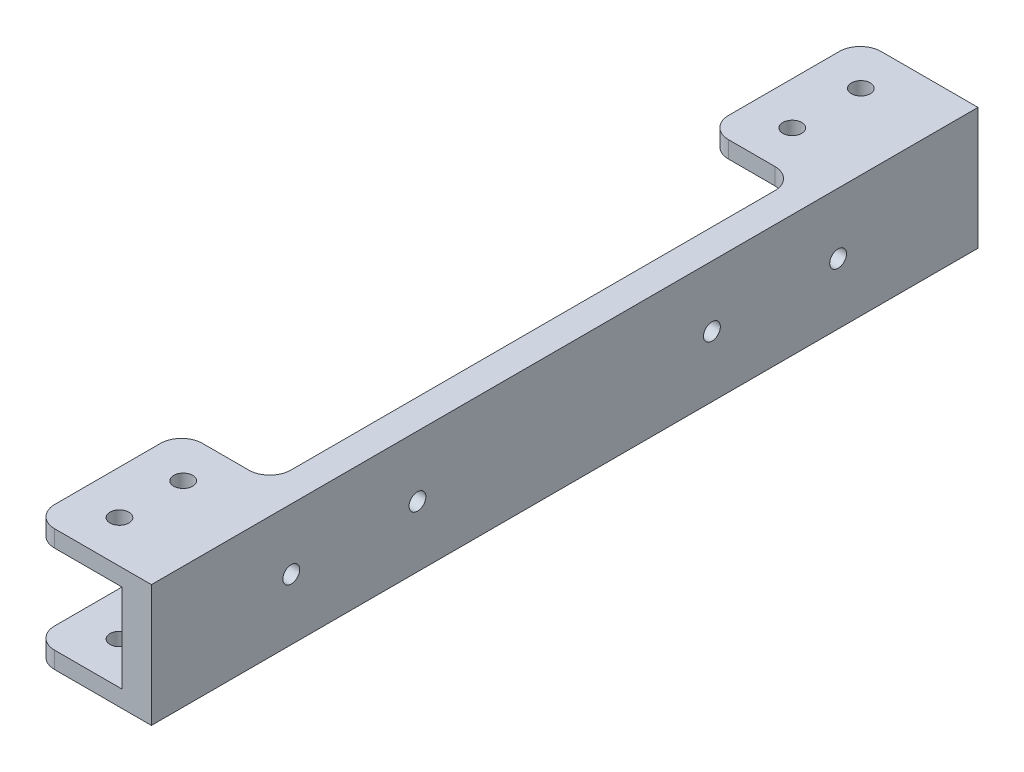
SolidWorks part; units mm, degrees
ref_plane "Front Plane" through (0, 0, 0) normal (0, 0, 1) x (1, 0, 0)
ref_plane "Top Plane" through (0, 0, 0) normal (0, 1, 0) x (1, 0, 0)
ref_plane "Right Plane" through (0, 0, 0) normal (1, 0, 0) x (0, 0, -1)
sketch "Sketch1" plane through (0, 0, 0) normal (0, 1, 0) x (1, 0, 0)
  line L0 (20, -143.5) -> (20, 143.5) construction
  line L1 (0, 143.5) -> (0, -143.5) construction
  point P0 (10.15, 87.9)
  point P1 (10.15, 71.6)
  point P4 (10.4, -88.6)
  point P5 (10.4, -73.45)
  point P8 (0, 0)
  point P13 (0, 0)
  dimension "D1" = 16.3
  dimension "D2" = 15.15
  dimension "D3" = 9.85
  dimension "D4" = 9.6
  dimension "D5" = 9.6
  dimension "D6" = 9.85
  dimension "D7" = 145.05
  dimension "D8" = 20
  dimension "D9" = 287
  dimension "D10" = 55.6
sketch "Sketch2" plane through (0, 0, 0) normal (0, 1, 0) x (1, 0, 0)
  line L0 (0, 97.9) -> (28, 97.9)
  line L1 (0, 143.5) -> (0, -143.5) construction
  line L2 (28, 97.9) -> (28, -98.6)
  line L3 (28, -98.6) -> (0, -98.6)
  line L4 (0, -98.6) -> (0, -63.45)
  line L5 (0, -63.45) -> (21, -63.45)
  line L7 (21, -63.45) -> (21, 61.6)
  line L8 (21, 61.6) -> (0, 61.6)
  line L9 (0, 61.6) -> (0, 97.9)
  line L10 (20, -143.5) -> (20, 143.5) construction
  point P4 (26.2377, 66.0287)
  point P9 (30.423, -66.2259)
  point P13 (0, 0)
  dimension "D1" = 1
  dimension "D2" = 7
  dimension "D3" = 10
  dimension "D4" = 10
  dimension "D5" = 10
  dimension "D6" = 10
extrude "Boss-Extrude1" add sketch "Sketch2" along normal blind 29
fillet "Fillet1" radius 5 6 edges at (0, 14.5, 98.6) (0, 14.5, 63.45) (0, 14.5, -61.6) (0, 14.5, -97.9) (21, 14.5, 63.45) (21, 14.5, -61.6)
sketch "Sketch3" plane through (0, 0, 0) normal (-1, 0, 0) x (0, 0, 1)
  line L5 (-97.9, 0) -> (-97.9, 29) construction
  line L6 (-97.9, 25) -> (98.6, 25)
  line L13 (-97.9, 25) -> (-97.9, 4)
  line L14 (-97.9, 4) -> (98.6, 4)
  line L18 (98.6, 25) -> (98.6, 4)
  line L19 (0.35, 4) -> (0.35, 25) construction
  line L20 (-97.9, 14.5) -> (98.6, 14.5) construction
  line L21 (98.6, 29) -> (98.6, 0) construction
  line L22 (-92.9, 29) -> (-66.6, 29) construction
  line L23 (-92.9, 0) -> (-66.6, 0) construction
  point P291 (0.35, 14.5)
  dimension "D1" = 4
  dimension "D2" = 4
extrude "Cut-Extrude1" cut sketch "Sketch3" against normal up to surface (21 mm away) up to face at (21, 14.5, 0.925)
sketch "Sketch6" plane through (0, 0, 0) normal (0, -1, 0) x (-1, 0, 0)
  point P0 (-10.15, 87.9)
  point P3 (-10.15, 71.6)
  point P6 (-10.4, -73.45)
  point P9 (-10.4, -88.6)
hole_wizard "M4 Clearance Hole1" positions "Sketch6" profile "Sketch5" hole size "M4" standard "DIN" end condition through all
sketch "Sketch5" plane through (10.15, 0, -87.9) normal (1, 0, 0) x (0, 0, -1)
  line L0 (0, 0) -> (0, 29)
  line L1 (0, 29) -> (2.25, 29)
  line L2 (2.25, 29) -> (2.25, 0)
  line L5 (2.25, 0) -> (0, 0)
  line L11 (0, -6.35) -> (0, 107.95) construction
  dimension "Thru Hole Dia." = 4.5
  dimension "Thru Hole Depth" = 29
sketch "Sketch7" plane through (21, 0, 0) normal (-1, 0, 0) x (0, 0, 1)
  line L0 (-97.9, 14.5) -> (98.6, 14.5) construction
  line L1 (-97.9, 25) -> (-97.9, 4) construction
  line L2 (98.6, 4) -> (98.6, 25) construction
  line L3 (0.35, 14.5) -> (0.35, 46.028) construction
  point P6 (-34.65, 14.5)
  point P7 (-64.65, 14.5)
  point P8 (35.35, 14.5)
  point P9 (65.35, 14.5)
  point P11 (0, 0)
  point P13 (0, 0)
  point P14 (0.35, 14.5)
  point P15 (-29.7695, 14.5)
  point P16 (-63.4126, 14.5)
  point P17 (-64.854, 14.5)
  point P18 (0, 0)
  dimension "D1" = 30
  dimension "D2" = 30
  dimension "D3" = 70
hole_wizard "Ø4.0mm Dowel Hole1" positions "Sketch7" profile "Sketch8" hole size "Ø4.0" standard "DIN" end condition through all
sketch "Sketch8" plane through (21, 14.5, 65.35) normal (0, 1, 0) x (0, 0, 1)
  line L0 (0, 0) -> (0, 7)
  line L1 (0, 7) -> (2, 7)
  line L2 (2, 7) -> (2, 0)
  line L5 (2, 0) -> (0, 0)
  line L11 (0, -6.35) -> (0, 107.95) construction
  dimension "Thru Hole Dia." = 4
  dimension "Thru Hole Depth" = 7
